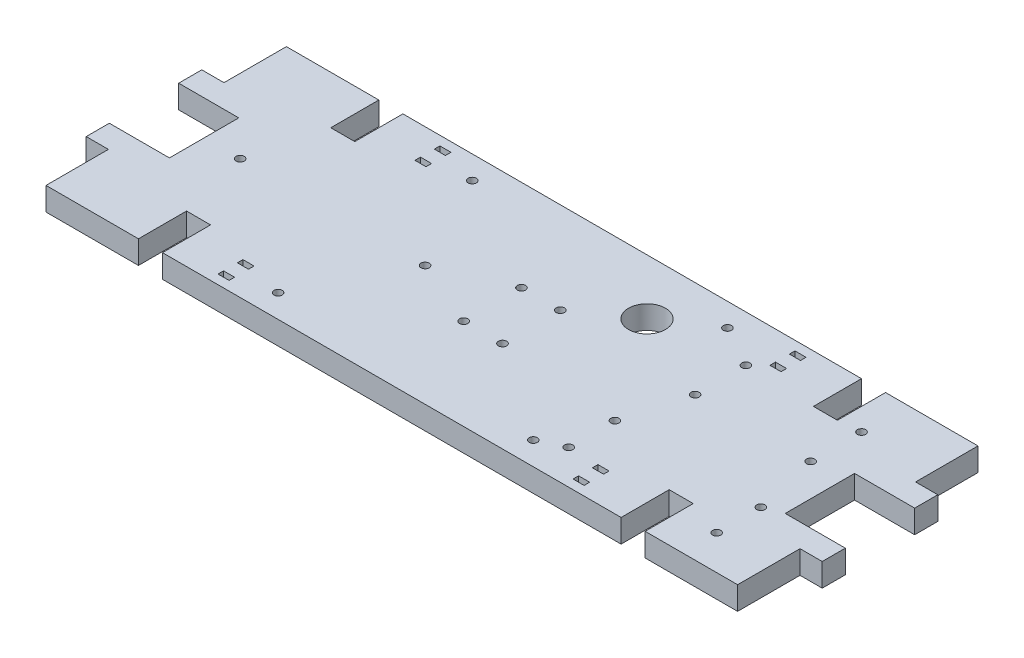
SolidWorks part; units mm, degrees
ref_plane "Front Plane" through (0, 0, 0) normal (0, 0, 1) x (1, 0, 0)
ref_plane "Top Plane" through (0, 0, 0) normal (0, 1, 0) x (1, 0, 0)
ref_plane "Right Plane" through (0, 0, 0) normal (1, 0, 0) x (0, 0, -1)
sketch "Sketch1" plane through (0, 0, 0) normal (0, 1, 0) x (1, 0, 0)
  line L0 (-95.504, 15.875) -> (-101.6, 15.875)
  line L1 (-95.504, 33.02) -> (-70.104, 33.02)
  line L2 (-95.504, 33.02) -> (-95.504, 15.875)
  line L3 (-95.504, -33.02) -> (-70.104, -33.02)
  line L4 (94.488, 33.02) -> (94.488, 15.875)
  line L5 (-101.6, 15.875) -> (-101.6, -15.875)
  line L6 (-101.6, -15.875) -> (-95.504, -15.875)
  line L7 (94.488, 15.875) -> (100.584, 15.875)
  line L8 (100.584, 15.875) -> (100.584, -15.875)
  line L9 (100.584, -15.875) -> (94.488, -15.875)
  line L10 (-63.5, 33.02) -> (2.794, 33.02)
  line L12 (-70.104, 33.02) -> (-70.104, 19.812)
  line L13 (-70.104, 19.812) -> (-63.5, 19.812)
  line L14 (-63.5, 33.02) -> (-63.5, 19.812)
  line L16 (-70.104, -33.02) -> (-70.104, -19.812)
  line L17 (-70.104, -19.812) -> (-63.5, -19.812)
  line L18 (-63.5, -33.02) -> (-63.5, -19.812)
  line L20 (62.484, 33.02) -> (62.484, 19.812)
  line L21 (62.484, 19.812) -> (69.088, 19.812)
  line L22 (69.088, 33.02) -> (69.088, 19.812)
  line L23 (62.484, -19.812) -> (69.088, -19.812)
  line L24 (62.484, -19.812) -> (62.484, -33.02)
  line L26 (69.088, -19.812) -> (69.088, -33.02)
  line L27 (69.088, 33.02) -> (94.488, 33.02)
  line L28 (69.088, -33.02) -> (94.488, -33.02)
  line L29 (94.488, -15.875) -> (94.488, -33.02)
  line L30 (-95.504, -15.875) -> (-95.504, -33.02)
  line L31 (-63.5, -33.02) -> (2.794, -33.02)
  line L38 (9.398, 33.02) -> (62.484, 33.02)
  line L39 (9.398, -33.02) -> (62.484, -33.02)
  line L40 (2.794, 33.02) -> (9.398, 33.02)
  line L41 (2.794, -33.02) -> (9.398, -33.02)
  dimension "D1" = 189.992
  dimension "D2" = 66.04
  dimension "D3" = 31.75
  dimension "D4" = 6.096
  dimension "D5" = 15.875
  dimension "D6" = 33.02
  dimension "D7" = 6.096
  dimension "D8" = 13.208
  dimension "D9" = 13.208
  dimension "D10" = 25.4
  dimension "D11" = 25.4
  dimension "D12" = 6.604
  dimension "D13" = 6.604
  dimension "D14" = 25.4
  dimension "D15" = 6.604
  dimension "D16" = 25.4
  dimension "D17" = 6.604
  dimension "D18" = 13.208
  dimension "D19" = 13.208
  dimension "D23" = 101.6
extrude "Boss-Extrude1" add sketch "Sketch1" along normal blind 6.35
sketch "Sketch2" plane through (0, 6.35, 0) normal (0, 1, 0) x (1, 0, 0)
  line L0 (-0.508, 33.02) -> (-0.508, -33.02) construction
  line L1 (62.484, 33.02) -> (-63.5, 33.02) construction
  line L2 (-63.5, -33.02) -> (62.484, -33.02) construction
  line L3 (-101.6, 0) -> (100.584, 0) construction
  line L4 (-101.6, 15.875) -> (-101.6, -15.875) construction
  line L5 (100.584, -15.875) -> (100.584, 15.875) construction
  line L6 (-95.504, -15.875) -> (-95.504, -33.02) construction
  line L7 (94.488, -33.02) -> (94.488, -15.875) construction
  circle A0 centre (-5.842, 7.9375) radius 1.1303
  circle A1 centre (4.826, 7.9375) radius 1.1303
  circle A2 centre (4.826, -7.9375) radius 1.1303
  circle A3 centre (-5.842, -7.9375) radius 1.1303
  circle A4 centre (-75.184, 0) radius 1.1303
  circle A5 centre (-24.384, 0) radius 1.1303
  circle A6 centre (43.434, 20.32) radius 1.1303
  circle A7 centre (75.184, 20.32) radius 1.1303
  circle A8 centre (75.184, 6.35) radius 1.1303
  circle A9 centre (43.434, 6.35) radius 1.1303
  circle A10 centre (38.608, -10.8394) radius 1.1303
  circle A11 centre (79.248, -11.3897) radius 1.1303
  circle A12 centre (38.608, -23.5394) radius 1.1303
  circle A13 centre (79.248, -23.5394) radius 1.1303
  dimension "D1" = 2.2606
  dimension "D2" = 2.2606
  dimension "D3" = 2.2606
  dimension "D4" = 2.2606
  dimension "D8" = 5.334
  dimension "D9" = 2.2606
  dimension "D10" = 2.2606
  dimension "D13" = 2.2606
  dimension "D14" = 2.2606
  dimension "D15" = 2.2606
  dimension "D16" = 2.2606
  dimension "D23" = 15.875
  dimension "D26" = 2.2606
  dimension "D27" = 2.2606
  dimension "D28" = 2.2606
  dimension "D29" = 2.2606
  dimension "D5" = 10.668
  dimension "D6" = 5.334
  dimension "D7" = 10.668
  dimension "D11" = 50.8
  dimension "D12" = 20.32
  dimension "D17" = 31.75
  dimension "D18" = 31.75
  dimension "D19" = 12.7
  dimension "D20" = 12.7
  dimension "D21" = 13.97
  dimension "D22" = 25.4
  dimension "D24" = 7.9375
  dimension "D25" = 25.4
  dimension "D30" = 12.7
  dimension "D31" = 40.64
  dimension "D32" = 15.24
  dimension "D33" = 15.24
extrude "Cut-Extrude1" cut sketch "Sketch2" against normal blind 10.16
sketch "Sketch3" plane through (0, 6.35, 0) normal (0, 1, 0) x (1, 0, 0)
  line L0 (62.484, 33.02) -> (-63.5, 33.02) construction
  line L1 (-50.8, 30.48) -> (-47.752, 30.48)
  line L2 (-50.8, 30.48) -> (-50.8, 28.956)
  line L3 (-50.8, 28.956) -> (-47.752, 28.956)
  line L4 (-47.752, 30.48) -> (-47.752, 28.956)
  line L5 (-50.8, 25.146) -> (-47.752, 25.146)
  line L6 (-50.8, 25.146) -> (-50.8, 23.622)
  line L7 (-50.8, 23.622) -> (-47.752, 23.622)
  line L8 (-47.752, 25.146) -> (-47.752, 23.622)
  line L9 (-63.5, 33.02) -> (-63.5, 19.812) construction
  line L10 (46.736, 30.48) -> (49.784, 30.48)
  line L11 (46.736, 30.48) -> (46.736, 28.956)
  line L12 (46.736, 28.956) -> (49.784, 28.956)
  line L13 (49.784, 30.48) -> (49.784, 28.956)
  line L14 (46.736, 25.146) -> (49.784, 25.146)
  line L15 (46.736, 25.146) -> (46.736, 23.622)
  line L16 (46.736, 23.622) -> (49.784, 23.622)
  line L17 (49.784, 25.146) -> (49.784, 23.622)
  line L18 (-50.8, 30.48) -> (46.736, 30.48) construction
  line L19 (-50.8, -23.622) -> (-47.752, -23.622)
  line L20 (-50.8, -23.622) -> (-50.8, -25.146)
  line L21 (-50.8, -25.146) -> (-47.752, -25.146)
  line L22 (-47.752, -23.622) -> (-47.752, -25.146)
  line L23 (-50.8, -28.956) -> (-47.752, -28.956)
  line L24 (-50.8, -28.956) -> (-50.8, -30.48)
  line L25 (-50.8, -30.48) -> (-47.752, -30.48)
  line L26 (-47.752, -28.956) -> (-47.752, -30.48)
  line L27 (46.736, -23.622) -> (49.784, -23.622)
  line L28 (46.736, -23.622) -> (46.736, -25.146)
  line L29 (46.736, -25.146) -> (49.784, -25.146)
  line L30 (49.784, -23.622) -> (49.784, -25.146)
  line L31 (46.736, -28.956) -> (49.784, -28.956)
  line L32 (46.736, -28.956) -> (46.736, -30.48)
  line L33 (46.736, -30.48) -> (49.784, -30.48)
  line L34 (49.784, -28.956) -> (49.784, -30.48)
  line L35 (-50.8, -23.622) -> (46.736, -23.622) construction
  line L36 (-50.8, 30.48) -> (-50.8, -23.622) construction
  line L37 (-63.5, -33.02) -> (62.484, -33.02) construction
  line L38 (-95.504, -15.875) -> (-95.504, -33.02) construction
  circle A0 centre (18.796, 17.78) radius 5.08
  dimension "D1" = 10.16
  dimension "D2" = 3.048
  dimension "D3" = 3.048
  dimension "D4" = 1.524
  dimension "D5" = 97.536
  dimension "D6" = 3.81
  dimension "D7" = 2.54
  dimension "D8" = 12.7
  dimension "D11" = 54.102
  dimension "D12" = 114.3
  dimension "D13" = 50.8
  dimension "D9" = 2
  dimension "D10" = 2
extrude "Cut-Extrude2" cut sketch "Sketch3" against normal blind 10.16
sketch "Sketch4" plane through (0, 6.35, 0) normal (0, 1, 0) x (1, 0, 0)
  line L0 (-63.5, 33.02) -> (-63.5, 19.812) construction
  line L1 (62.484, 33.02) -> (-63.5, 33.02) construction
  circle A0 centre (-38.1, 26.67) radius 1.1303
  circle A1 centre (32.004, 26.67) radius 1.1303
  circle A2 centre (-38.1, -26.67) radius 1.1303
  circle A3 centre (32.004, -26.67) radius 1.1303
  dimension "D1" = 2.2606
  dimension "D2" = 25.4
  dimension "D3" = 6.35
  dimension "D4" = 2
  dimension "D5" = 2
extrude "Cut-Extrude3" cut sketch "Sketch4" against normal blind 10.16
sketch "Sketch5" plane through (0, 6.35, 0) normal (0, 1, 0) x (1, 0, 0)
  line L0 (-101.6, 9.525) -> (-85.09, 9.525)
  line L1 (-101.6, 15.875) -> (-101.6, -15.875) construction
  line L2 (-85.09, 9.525) -> (-85.09, -9.525)
  line L3 (-85.09, -9.525) -> (-101.6, -9.525)
  line L4 (-101.6, -9.525) -> (-101.6, 9.525)
  line L5 (-95.504, 15.875) -> (-101.6, 15.875) construction
  line L6 (-101.6, -15.875) -> (-95.504, -15.875) construction
  line L7 (100.584, -15.875) -> (100.584, 15.875) construction
  line L8 (100.584, 9.525) -> (84.074, 9.525)
  line L9 (100.584, 9.525) -> (100.584, -9.525)
  line L10 (100.584, -9.525) -> (84.074, -9.525)
  line L11 (84.074, 9.525) -> (84.074, -9.525)
  line L12 (100.584, 15.875) -> (94.488, 15.875) construction
  line L13 (94.488, -15.875) -> (100.584, -15.875) construction
  dimension "D1" = 16.51
  dimension "D2" = 6.35
  dimension "D3" = 6.35
  dimension "D4" = 16.51
  dimension "D5" = 6.35
  dimension "D6" = 6.35
extrude "Cut-Extrude4" cut sketch "Sketch5" against normal blind 10.16
